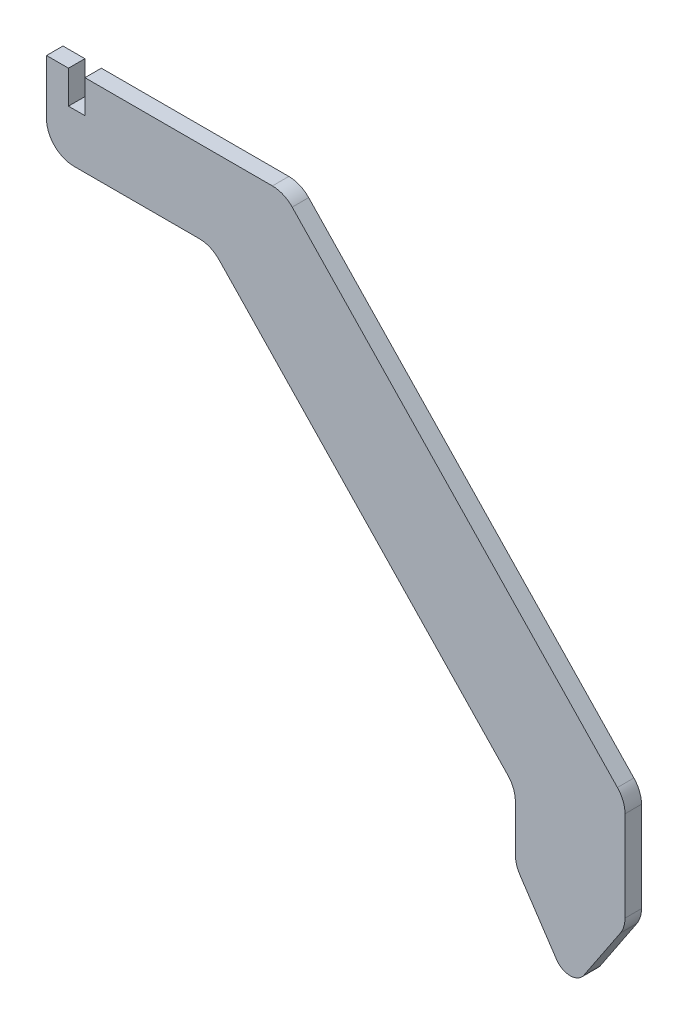
SolidWorks part; units mm, degrees
material "PBT General Purpose"
ref_plane "Front Plane" through (0, 0, 0) normal (0, 0, 1) x (1, 0, 0)
ref_plane "Top Plane" through (0, 0, 0) normal (0, 1, 0) x (1, 0, 0)
ref_plane "Right Plane" through (0, 0, 0) normal (1, 0, 0) x (0, 0, -1)
sketch "Sketch1" plane through (0, 0, 0) normal (0, 0, 1) x (1, 0, 0)
  line L13 (0, 0) -> (0.4, 0)
  line L14 (4.3328, 0) -> (10.55, -6.5)
  line L15 (10.55, -6.5) -> (10.55, -8.5)
  line L16 (10.55, -8.5) -> (9.55, -10)
  line L17 (9.55, -10) -> (8.55, -8.5)
  line L18 (8.55, -8.5) -> (8.55, -7.3025)
  line L19 (8.55, -7.3025) -> (3, -1.5)
  line L20 (3, -1.5) -> (0, -1.5)
  line L21 (0, -1.5) -> (0, 0)
  line L22 (0.4, 0) -> (0.4, -0.6)
  line L23 (0.4, -0.6) -> (0.7, -0.6)
  line L24 (0.7, -0.6) -> (0.7, 0)
  line L25 (0.7, 0) -> (4.3328, 0)
  line L26 (10.55, -8.5) -> (8.55, -8.5) construction
  point P13 (0.55, -0.6)
  point P16 (9.55, -8.5)
  dimension "D1" = 0.3
  dimension "D3" = 1.5
  dimension "D4" = 0.4
  dimension "D5" = 9
  dimension "D6" = 10
  dimension "D7" = 2
  dimension "D8" = 2
  dimension "D2" = 0.6
  dimension "D9" = 2
  dimension "D10" = 3
  dimension "D11" = 1.5
extrude "Boss-Extrude1" add sketch "Sketch1" along normal mid plane 0.3
fillet "Fillet1" radius 0.3 1 edges at (9.55, -10, 0)
fillet "Fillet2" radius 0.5 7 edges at (0, -1.5, 0) (4.3328, 0, 0) (10.55, -6.5, 0) (10.55, -8.5, 0) (8.55, -8.5, 0) (8.55, -7.3025, 0) (3, -1.5, 0)
equation "\"t\"= 0.3'thickness of the sheets"
equation "\"FlexJoint\"= 0.15'Width of flextures"
equation "\"FoldJoint\"= 0.4'Width of folding joints"
equation "\"AssembleAngle\"= 90'Angle of assembly parts"
equation "\"D1@Boss-Extrude1\"=\"t\""
equation "\"D1@Sketch1\"=\"t\""
